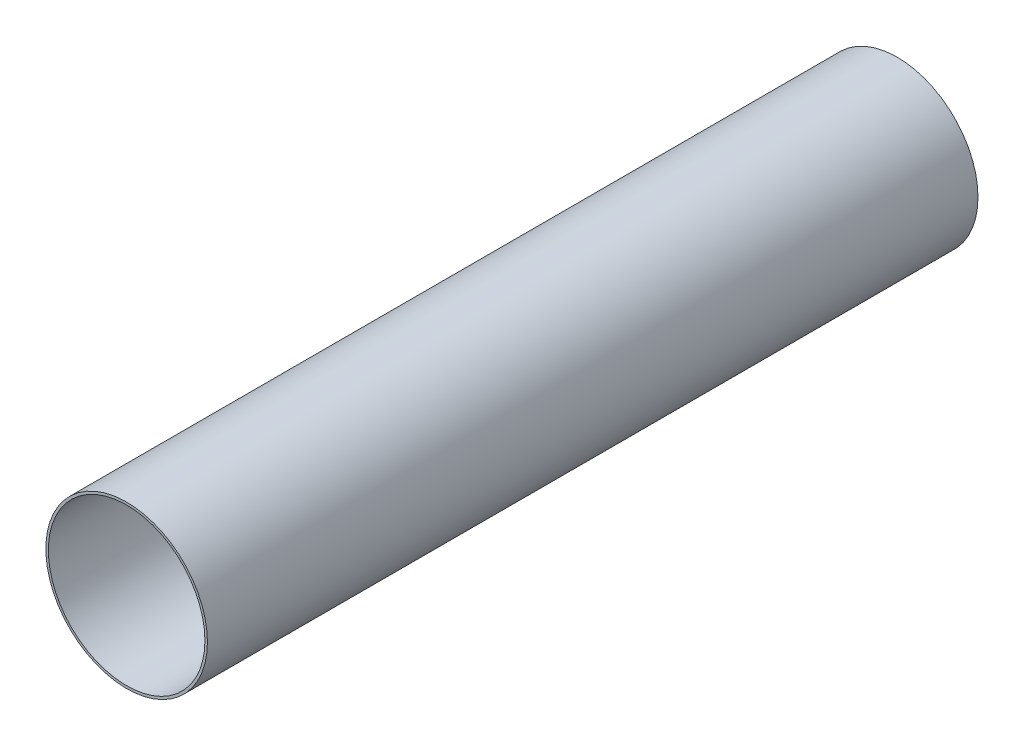
SolidWorks part; units mm, degrees
material "Plástico personalizado"
ref_plane "Plano frontal" through (0, 0, 0) normal (0, 0, 1) x (1, 0, 0)
ref_plane "Plano superior" through (0, 0, 0) normal (0, 1, 0) x (1, 0, 0)
ref_plane "Plano direito" through (0, 0, 0) normal (1, 0, 0) x (0, 0, -1)
sketch "Esboço1" plane through (0, 0, 0) normal (0, 0, 1) x (1, 0, 0)
  circle A0 centre (0, 0) radius 32.5
  circle A1 centre (0, 0) radius 31.5
extrude "Ressalto-extrusão1" add sketch "Esboço1" along normal blind 310
